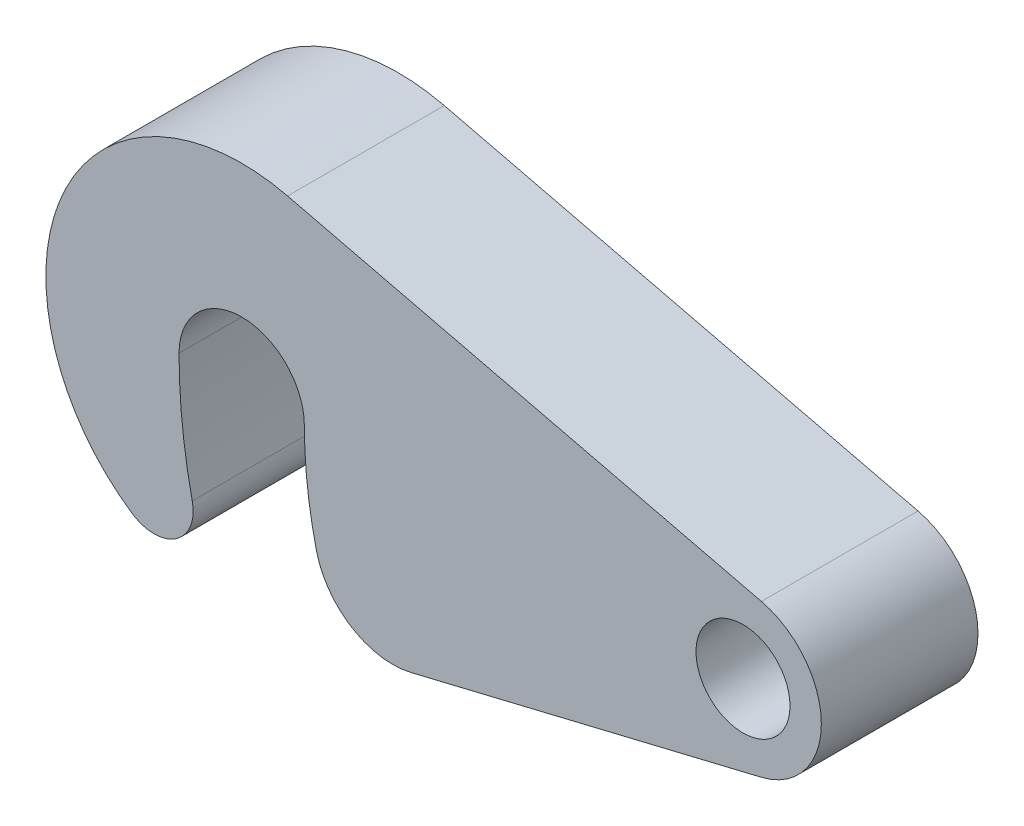
SolidWorks part; units mm, degrees
ref_plane "Front Plane" through (0, 0, 0) normal (0, 0, 1) x (1, 0, 0)
ref_plane "Top Plane" through (0, 0, 0) normal (0, 1, 0) x (1, 0, 0)
ref_plane "Right Plane" through (0, 0, 0) normal (1, 0, 0) x (0, 0, -1)
sketch "Sketch1" plane through (0, 0, 0) normal (0, 0, 1) x (1, 0, 0)
  line L0 (0, 0) -> (0, 34589.26) construction
  line L1 (0, 0) -> (34589.26, 0) construction
  line L2 (5.8594, 24.3037) -> (66.3438, 9.7215)
  line L3 (21.625, -20.5027) -> (66.3438, -9.7215)
  circle A0 centre (64, 0) radius 6
  arc A1 (66.3438, -9.7215) -> (66.3438, 9.7215) centre (64, 0) ccw
  arc A2 (8, 0) -> (-8, 0) centre (0, 0) ccw
  arc A3 (5.8594, 24.3037) -> (-13.9941, -20.7163) centre (0, 0) ccw
  arc A4 (8, 0) -> (9.5598, -13.125) centre (64, 0) ccw
  arc A5 (-8, 0) -> (-6.3125, -15.4968) centre (64, 0) ccw
  arc A6 (21.625, -20.5027) -> (9.5598, -13.125) centre (19.2813, -10.7813) cw
  arc A7 (-13.9941, -20.7163) -> (-6.3125, -15.4968) centre (-11.1953, -16.573) ccw
  dimension "D1" = 64
  dimension "D2" = 12
  dimension "D3" = 20
  dimension "D4" = 16
  dimension "D5" = 50
  dimension "D6" = 10
  dimension "D7" = 5
extrude "Boss-Extrude1" add sketch "Sketch1" along normal mid plane 20
